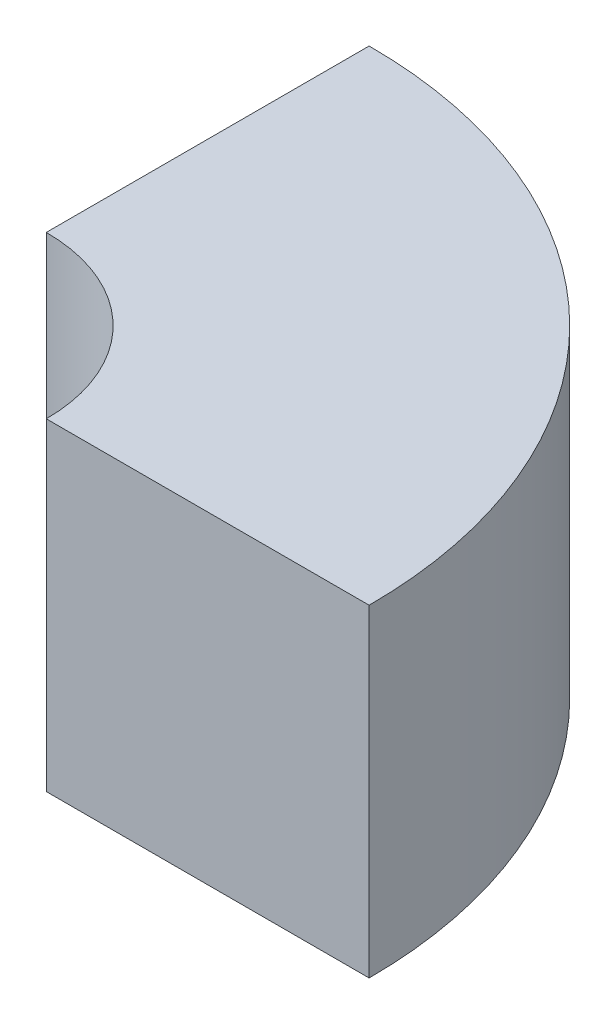
SolidWorks part; units mm, degrees
ref_plane "前视基准面" through (0, 0, 0) normal (0, 0, 1) x (1, 0, 0)
ref_plane "上视基准面" through (0, 0, 0) normal (0, 1, 0) x (1, 0, 0)
ref_plane "右视基准面" through (0, 0, 0) normal (1, 0, 0) x (0, 0, -1)
other "Configuration Table"
sketch "草图1" plane through (0, 0, 0) normal (0, 0, 1) x (1, 0, 0)
  line L0 (0, 0) -> (0, 20) construction
  line L2 (5, 0) -> (15, 0)
  line L3 (5, 0) -> (5, 10)
  line L4 (5, 10) -> (15, 10)
  line L5 (15, 0) -> (15, 10)
revolve "旋转1" add sketch "草图1" angle 90 about L0
